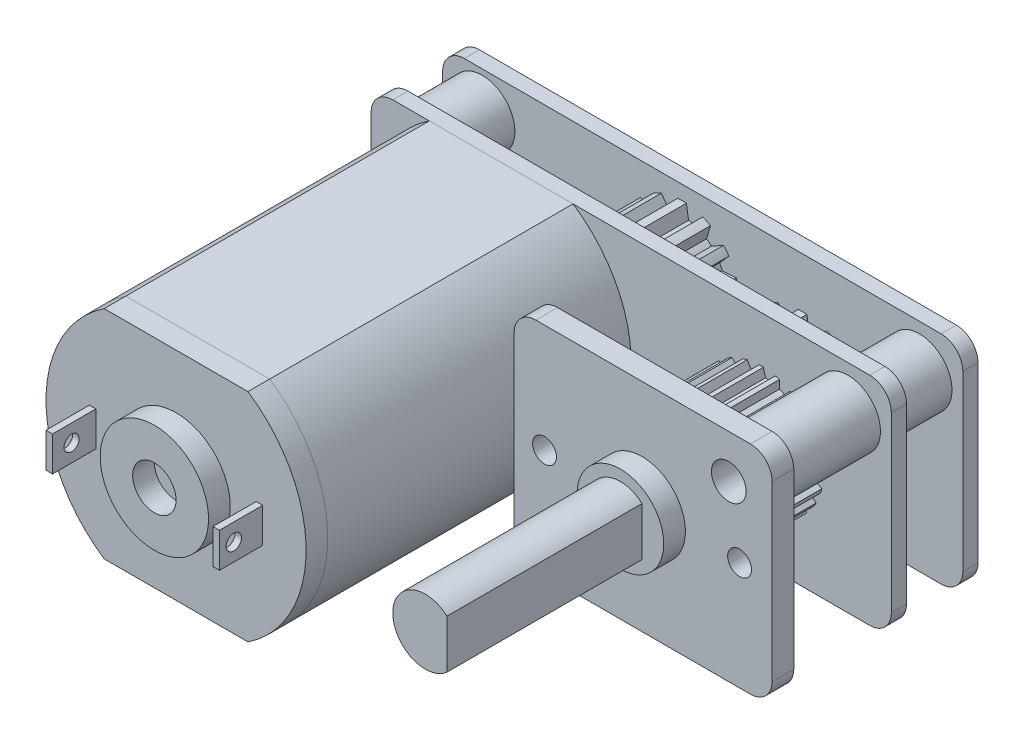
SolidWorks part; units mm, degrees
ref_plane "前视基准面" through (0, 0, 0) normal (0, 0, 1) x (1, 0, 0)
ref_plane "上视基准面" through (0, 0, 0) normal (0, 1, 0) x (1, 0, 0)
ref_plane "右视基准面" through (0, 0, 0) normal (1, 0, 0) x (0, 0, -1)
sketch "草图1" plane through (0, 0, 0) normal (0, 0, 1) x (1, 0, 0)
  line L0 (0, 0) -> (18.8291, 0) construction
  line L1 (-3.3166, 5) -> (3.3166, 5)
  line L3 (-3.3166, -5) -> (3.3166, -5)
  arc A0 (-3.3166, 5) -> (-3.3166, -5) centre (0, 0) ccw
  arc A1 (3.3166, -5) -> (3.3166, 5) centre (0, 0) ccw
  dimension "D1" = 12
  dimension "D2" = 10
extrude "凸台-拉伸1" add sketch "草图1" along normal blind 14
sketch "草图2" plane through (0, 0, 14) normal (0, 0, 1) x (1, 0, 0)
  line L2 (-3.3166, -5) -> (3.3166, -5)
  line L3 (3.3166, 5) -> (-3.3166, 5)
  line L4 (-3.3166, -5) -> (3.3166, -5)
  line L5 (3.3166, 5) -> (-3.3166, 5)
  arc A2 (-3.3166, 5) -> (-3.3166, -5) centre (0, 0) ccw
  arc A3 (3.3166, -5) -> (3.3166, 5) centre (0, 0) ccw
  arc A4 (-3.3166, 5) -> (-3.3166, -5) centre (0, 0) ccw
  arc A5 (3.3166, -5) -> (3.3166, 5) centre (0, 0) ccw
  dimension "D1" = 0
extrude "凸台-拉伸2" add sketch "草图2" along normal blind 1 separate body
sketch "草图3" plane through (0, 0, 15) normal (0, 0, 1) x (1, 0, 0)
  circle A0 centre (0, 0) radius 2.5
  circle A1 centre (0, 0) radius 1
  dimension "D1" = 5
  dimension "D2" = 2
extrude "凸台-拉伸3" add sketch "草图3" along normal blind 1
sketch "草图4" plane through (0, 0, 15) normal (0, 0, 1) x (1, 0, 0)
  line L0 (0, 0) -> (0, 3.9514) construction
  line L1 (-4, 0.8) -> (-3.7, 0.8)
  line L2 (-4, 0.8) -> (-4, -0.8)
  line L3 (-4, -0.8) -> (-3.7, -0.8)
  line L4 (-3.7, 0.8) -> (-3.7, -0.8)
  line L5 (0, 0) -> (-8.2153, 0) construction
  line L6 (3.7, 0.8) -> (3.7, -0.8)
  line L7 (4, -0.8) -> (3.7, -0.8)
  line L8 (4, 0.8) -> (4, -0.8)
  line L9 (4, 0.8) -> (3.7, 0.8)
  dimension "D1" = 1.6
  dimension "D2" = 0.3
  dimension "D3" = 4
extrude "凸台-拉伸4" add sketch "草图4" along normal blind 2 separate body
sketch "草图5" plane through (-4, 0, 0) normal (-1, 0, 0) x (0, 0, 1)
  circle A0 centre (16.1189, 0) radius 0.35
  dimension "D1" = 0.7
extrude "切除-拉伸1" cut sketch "草图5" against normal blind 1
sketch "草图6" plane through (4, 0, 0) normal (1, 0, 0) x (0, 0, -1)
  circle A0 centre (-16.3339, 0) radius 0.3561
  dimension "D1" = 0.7122
extrude "切除-拉伸2" cut sketch "草图6" against normal blind 1
sketch "草图7" plane through (0, 0, 0) normal (0, 0, -1) x (-1, 0, 0)
  line L0 (0, 0) -> (0, 7.3906) construction
  line L1 (-17, 5) -> (5, 5)
  line L2 (-18, 4) -> (-18, -4)
  line L3 (-17, -5) -> (5, -5)
  line L4 (6, 4) -> (6, -4)
  line L5 (0, 0) -> (-12.0112, 0) construction
  arc A0 (-18, -4) -> (-17, -5) centre (-17, -4) ccw
  arc A1 (5, -5) -> (6, -4) centre (5, -4) ccw
  arc A2 (6, 4) -> (5, 5) centre (5, 4) ccw
  arc A3 (-17, 5) -> (-18, 4) centre (-17, 4) ccw
  point P10 (-18, -5)
  point P15 (6, 5)
  point P18 (-18, 5)
  dimension "D3" = 1
  dimension "D1" = 10
  dimension "D2" = 24
  dimension "D4" = 6
extrude "凸台-拉伸5" add sketch "草图7" along normal blind 0.7 separate body
sketch "草图8" plane through (0, 0, -0.7) normal (0, 0, -1) x (-1, 0, 0)
  line L0 (0, 0) -> (0, 2.0594) construction
  line L1 (0, 2.1498) -> (0.1718, 1.6344)
  line L2 (0, 2.1498) -> (-0.1718, 1.6344)
  line L3 (0.447, 2.1028) -> (0.5078, 1.563)
  line L4 (0.447, 2.1028) -> (0.1718, 1.6344)
  line L5 (0.8744, 1.9639) -> (0.8217, 1.4232)
  line L6 (0.8744, 1.9639) -> (0.5078, 1.563)
  line L7 (1.2636, 1.7392) -> (1.0997, 1.2213)
  line L8 (1.2636, 1.7392) -> (0.8217, 1.4232)
  line L9 (1.5976, 1.4385) -> (1.3296, 0.966)
  line L10 (1.5976, 1.4385) -> (1.0997, 1.2213)
  line L11 (1.8618, 1.0749) -> (1.5013, 0.6684)
  line L12 (1.8618, 1.0749) -> (1.3296, 0.966)
  line L13 (2.0446, 0.6643) -> (1.6075, 0.3417)
  line L14 (2.0446, 0.6643) -> (1.5013, 0.6684)
  line L15 (2.138, 0.2247) -> (1.6434, 0)
  line L16 (2.138, 0.2247) -> (1.6075, 0.3417)
  line L17 (2.138, -0.2247) -> (1.6075, -0.3417)
  line L18 (2.138, -0.2247) -> (1.6434, 0)
  line L19 (2.0446, -0.6643) -> (1.5013, -0.6684)
  line L20 (2.0446, -0.6643) -> (1.6075, -0.3417)
  line L21 (1.8618, -1.0749) -> (1.3296, -0.966)
  line L22 (1.8618, -1.0749) -> (1.5013, -0.6684)
  line L23 (1.5976, -1.4385) -> (1.0997, -1.2213)
  line L24 (1.5976, -1.4385) -> (1.3296, -0.966)
  line L25 (1.2636, -1.7392) -> (0.8217, -1.4232)
  line L26 (1.2636, -1.7392) -> (1.0997, -1.2213)
  line L27 (0.8744, -1.9639) -> (0.5078, -1.563)
  line L28 (0.8744, -1.9639) -> (0.8217, -1.4232)
  line L29 (0.447, -2.1028) -> (0.1718, -1.6344)
  line L30 (0.447, -2.1028) -> (0.5078, -1.563)
  line L31 (0, -2.1498) -> (-0.1718, -1.6344)
  line L32 (0, -2.1498) -> (0.1718, -1.6344)
  line L33 (-0.447, -2.1028) -> (-0.5078, -1.563)
  line L34 (-0.447, -2.1028) -> (-0.1718, -1.6344)
  line L35 (-0.8744, -1.9639) -> (-0.8217, -1.4232)
  line L36 (-0.8744, -1.9639) -> (-0.5078, -1.563)
  line L37 (-1.2636, -1.7392) -> (-1.0997, -1.2213)
  line L38 (-1.2636, -1.7392) -> (-0.8217, -1.4232)
  line L39 (-1.5976, -1.4385) -> (-1.3296, -0.966)
  line L40 (-1.5976, -1.4385) -> (-1.0997, -1.2213)
  line L41 (-1.8618, -1.0749) -> (-1.5013, -0.6684)
  line L42 (-1.8618, -1.0749) -> (-1.3296, -0.966)
  line L43 (-2.0446, -0.6643) -> (-1.6075, -0.3417)
  line L44 (-2.0446, -0.6643) -> (-1.5013, -0.6684)
  line L45 (-2.138, -0.2247) -> (-1.6434, 0)
  line L46 (-2.138, -0.2247) -> (-1.6075, -0.3417)
  line L47 (-2.138, 0.2247) -> (-1.6075, 0.3417)
  line L48 (-2.138, 0.2247) -> (-1.6434, 0)
  line L49 (-2.0446, 0.6643) -> (-1.5013, 0.6684)
  line L50 (-2.0446, 0.6643) -> (-1.6075, 0.3417)
  line L51 (-1.8618, 1.0749) -> (-1.3296, 0.966)
  line L52 (-1.8618, 1.0749) -> (-1.5013, 0.6684)
  line L53 (-1.5976, 1.4385) -> (-1.0997, 1.2213)
  line L54 (-1.5976, 1.4385) -> (-1.3296, 0.966)
  line L55 (-1.2636, 1.7392) -> (-0.8217, 1.4232)
  line L56 (-1.2636, 1.7392) -> (-1.0997, 1.2213)
  line L57 (-0.8744, 1.9639) -> (-0.5078, 1.563)
  line L58 (-0.8744, 1.9639) -> (-0.8217, 1.4232)
  line L59 (-0.447, 2.1028) -> (-0.1718, 1.6344)
  line L60 (-0.447, 2.1028) -> (-0.5078, 1.563)
  point P96 (0, 0)
extrude "凸台-拉伸6" add sketch "草图8" along normal blind 2.5
sketch "草图9" plane through (0, 0, -0.7) normal (0, 0, -1) x (-1, 0, 0)
  circle A0 centre (4.1671, 3.2475) radius 1.5
  circle A1 centre (-4.1288, -3.2666) radius 1.5
  dimension "D1" = 3
  dimension "D2" = 3
extrude "凸台-拉伸7" add sketch "草图9" along normal blind 2.6
sketch "草图10" plane through (0, 0, -3.3) normal (0, 0, -1) x (-1, 0, 0)
  line L0 (0, 0) -> (0, 6.111) construction
  line L1 (-17, 5) -> (5, 5)
  line L2 (-18, 4) -> (-18, -4)
  line L3 (-17, -5) -> (5, -5)
  line L4 (6, 4) -> (6, -4)
  line L5 (0, 0) -> (8.0146, 0) construction
  arc A0 (-18, -4) -> (-17, -5) centre (-17, -4) ccw
  arc A1 (5, -5) -> (6, -4) centre (5, -4) ccw
  arc A2 (6, 4) -> (5, 5) centre (5, 4) ccw
  arc A3 (-17, 5) -> (-18, 4) centre (-17, 4) ccw
  point P10 (-18, -5)
  point P15 (6, 5)
  point P18 (-18, 5)
  dimension "D3" = 1
  dimension "D1" = 10
  dimension "D2" = 24
  dimension "D4" = 6
extrude "凸台-拉伸8" add sketch "草图10" along normal blind 0.7
sketch "草图11" plane through (0, 0, -4) normal (0, 0, -1) x (-1, 0, 0)
  line L0 (-18, 4) -> (-18, -4) construction
  line L1 (5, 5) -> (-17, 5) construction
  line L2 (-17, -5) -> (5, -5) construction
  circle A0 centre (-16, 3) radius 1.5
  circle A1 centre (-8, -3) radius 1.5
  circle A2 centre (-16, 3) radius 0.8
  circle A3 centre (-8, -3) radius 0.8
  dimension "D1" = 2
  dimension "D2" = 2
  dimension "D3" = 3
  dimension "D4" = 1.6
  dimension "D6" = 2
  dimension "D7" = 3
  dimension "D8" = 1.6
  dimension "D5" = 10
extrude "凸台-拉伸9" add sketch "草图11" against normal blind 9.5
sketch "草图17" plane through (0, 0, 0) normal (0, 0, 1) x (1, 0, 0)
  line L0 (18, 4) -> (18, -4) construction
  line L1 (-5, 5) -> (17, 5) construction
  line L2 (12, 0) -> (12, 3.9728) construction
  line L3 (11.9, 2.8644) -> (11.8, 2.492)
  line L4 (12.1, 2.8644) -> (12.2, 2.492)
  line L5 (12.6448, 2.7927) -> (12.4518, 2.4588)
  line L6 (12.8379, 2.7409) -> (12.8382, 2.3553)
  line L7 (13.3456, 2.5306) -> (13.0728, 2.2581)
  line L8 (13.5188, 2.4306) -> (13.4192, 2.0581)
  line L9 (13.9547, 2.0961) -> (13.6207, 1.9035)
  line L10 (14.0961, 1.9547) -> (13.9035, 1.6207)
  line L11 (14.4306, 1.5188) -> (14.0581, 1.4192)
  line L12 (14.5306, 1.3456) -> (14.2581, 1.0728)
  line L13 (14.7409, 0.8379) -> (14.3553, 0.8382)
  line L14 (14.7927, 0.6448) -> (14.4588, 0.4518)
  line L15 (14.8644, 0.1) -> (14.492, 0.2)
  line L16 (14.8644, -0.1) -> (14.492, -0.2)
  line L17 (14.7927, -0.6448) -> (14.4588, -0.4518)
  line L18 (14.7409, -0.8379) -> (14.3553, -0.8382)
  line L19 (14.5306, -1.3456) -> (14.2581, -1.0728)
  line L20 (14.4306, -1.5188) -> (14.0581, -1.4192)
  line L21 (14.0961, -1.9547) -> (13.9035, -1.6207)
  line L22 (13.9547, -2.0961) -> (13.6207, -1.9035)
  line L23 (13.5188, -2.4306) -> (13.4192, -2.0581)
  line L24 (13.3456, -2.5306) -> (13.0728, -2.2581)
  line L25 (12.8379, -2.7409) -> (12.8382, -2.3553)
  line L26 (12.6448, -2.7927) -> (12.4518, -2.4588)
  line L27 (12.1, -2.8644) -> (12.2, -2.492)
  line L28 (11.9, -2.8644) -> (11.8, -2.492)
  line L29 (11.3552, -2.7927) -> (11.5482, -2.4588)
  line L30 (11.1621, -2.7409) -> (11.1618, -2.3553)
  line L31 (10.6544, -2.5306) -> (10.9272, -2.2581)
  line L32 (10.4812, -2.4306) -> (10.5808, -2.0581)
  line L33 (10.0453, -2.0961) -> (10.3793, -1.9035)
  line L34 (9.9039, -1.9547) -> (10.0965, -1.6207)
  line L35 (9.5694, -1.5188) -> (9.9419, -1.4192)
  line L36 (9.4694, -1.3456) -> (9.7419, -1.0728)
  line L37 (9.2591, -0.8379) -> (9.6447, -0.8382)
  line L38 (9.2073, -0.6448) -> (9.5412, -0.4518)
  line L39 (9.1356, -0.1) -> (9.508, -0.2)
  line L40 (9.1356, 0.1) -> (9.508, 0.2)
  line L41 (9.2073, 0.6448) -> (9.5412, 0.4518)
  line L42 (9.2591, 0.8379) -> (9.6447, 0.8382)
  line L43 (9.4694, 1.3456) -> (9.7419, 1.0728)
  line L44 (9.5694, 1.5188) -> (9.9419, 1.4192)
  line L45 (9.9039, 1.9547) -> (10.0965, 1.6207)
  line L46 (10.0453, 2.0961) -> (10.3793, 1.9035)
  line L47 (10.4812, 2.4306) -> (10.5808, 2.0581)
  line L48 (10.6544, 2.5306) -> (10.9272, 2.2581)
  line L49 (11.1621, 2.7409) -> (11.1618, 2.3553)
  line L50 (11.3552, 2.7927) -> (11.5482, 2.4588)
  arc A0 (11.1618, 2.3553) -> (10.9272, 2.2581) centre (12, 0) ccw
  arc A1 (12.1, 2.8644) -> (11.9, 2.8644) centre (12, 0) ccw
  arc A2 (12.8379, 2.7409) -> (12.6448, 2.7927) centre (12, 0) ccw
  arc A3 (13.5188, 2.4306) -> (13.3456, 2.5306) centre (12, 0) ccw
  arc A4 (14.0961, 1.9547) -> (13.9547, 2.0961) centre (12, 0) ccw
  arc A5 (14.5306, 1.3456) -> (14.4306, 1.5188) centre (12, 0) ccw
  arc A6 (14.7927, 0.6448) -> (14.7409, 0.8379) centre (12, 0) ccw
  arc A7 (14.8644, -0.1) -> (14.8644, 0.1) centre (12, 0) ccw
  arc A8 (14.7409, -0.8379) -> (14.7927, -0.6448) centre (12, 0) ccw
  arc A9 (14.4306, -1.5188) -> (14.5306, -1.3456) centre (12, 0) ccw
  arc A10 (13.9547, -2.0961) -> (14.0961, -1.9547) centre (12, 0) ccw
  arc A11 (13.3456, -2.5306) -> (13.5188, -2.4306) centre (12, 0) ccw
  arc A12 (12.6448, -2.7927) -> (12.8379, -2.7409) centre (12, 0) ccw
  arc A13 (11.9, -2.8644) -> (12.1, -2.8644) centre (12, 0) ccw
  arc A14 (11.1621, -2.7409) -> (11.3552, -2.7927) centre (12, 0) ccw
  arc A15 (10.4812, -2.4306) -> (10.6544, -2.5306) centre (12, 0) ccw
  arc A16 (9.9039, -1.9547) -> (10.0453, -2.0961) centre (12, 0) ccw
  arc A17 (9.4694, -1.3456) -> (9.5694, -1.5188) centre (12, 0) ccw
  arc A18 (9.2073, -0.6448) -> (9.2591, -0.8379) centre (12, 0) ccw
  arc A19 (9.1356, 0.1) -> (9.1356, -0.1) centre (12, 0) ccw
  arc A20 (9.2591, 0.8379) -> (9.2073, 0.6448) centre (12, 0) ccw
  arc A21 (9.5694, 1.5188) -> (9.4694, 1.3456) centre (12, 0) ccw
  arc A22 (10.0453, 2.0961) -> (9.9039, 1.9547) centre (12, 0) ccw
  arc A23 (10.6544, 2.5306) -> (10.4812, 2.4306) centre (12, 0) ccw
  arc A24 (11.3552, 2.7927) -> (11.1621, 2.7409) centre (12, 0) ccw
  arc A25 (10.5808, 2.0581) -> (10.3793, 1.9035) centre (12, 0) ccw
  arc A26 (10.0965, 1.6207) -> (9.9419, 1.4192) centre (12, 0) ccw
  arc A27 (9.7419, 1.0728) -> (9.6447, 0.8382) centre (12, 0) ccw
  arc A28 (9.5412, 0.4518) -> (9.508, 0.2) centre (12, 0) ccw
  arc A29 (9.508, -0.2) -> (9.5412, -0.4518) centre (12, 0) ccw
  arc A30 (9.6447, -0.8382) -> (9.7419, -1.0728) centre (12, 0) ccw
  arc A31 (9.9419, -1.4192) -> (10.0965, -1.6207) centre (12, 0) ccw
  arc A32 (10.3793, -1.9035) -> (10.5808, -2.0581) centre (12, 0) ccw
  arc A33 (10.9272, -2.2581) -> (11.1618, -2.3553) centre (12, 0) ccw
  arc A34 (11.5482, -2.4588) -> (11.8, -2.492) centre (12, 0) ccw
  arc A35 (12.2, -2.492) -> (12.4518, -2.4588) centre (12, 0) ccw
  arc A36 (12.8382, -2.3553) -> (13.0728, -2.2581) centre (12, 0) ccw
  arc A37 (13.4192, -2.0581) -> (13.6207, -1.9035) centre (12, 0) ccw
  arc A38 (13.9035, -1.6207) -> (14.0581, -1.4192) centre (12, 0) ccw
  arc A39 (14.2581, -1.0728) -> (14.3553, -0.8382) centre (12, 0) ccw
  arc A40 (14.4588, -0.4518) -> (14.492, -0.2) centre (12, 0) ccw
  arc A41 (14.492, 0.2) -> (14.4588, 0.4518) centre (12, 0) ccw
  arc A42 (14.3553, 0.8382) -> (14.2581, 1.0728) centre (12, 0) ccw
  arc A43 (14.0581, 1.4192) -> (13.9035, 1.6207) centre (12, 0) ccw
  arc A44 (13.6207, 1.9035) -> (13.4192, 2.0581) centre (12, 0) ccw
  arc A45 (13.0728, 2.2581) -> (12.8382, 2.3553) centre (12, 0) ccw
  arc A46 (12.4518, 2.4588) -> (12.2, 2.492) centre (12, 0) ccw
  arc A47 (11.8, 2.492) -> (11.5482, 2.4588) centre (12, 0) ccw
  point P106 (12, 0)
  dimension "D1" = 6
  dimension "D2" = 5
  dimension "D3" = 5
  dimension "D4" = 0.2
  dimension "D5" = 0.4
  dimension "D6" = 24
extrude "凸台-拉伸15" add sketch "草图17" along normal blind 4.5 separate body
sketch "草图13" plane through (0, 0, 5.5) normal (0, 0, 1) x (1, 0, 0)
  line L1 (7.1, 5) -> (17, 5)
  line L2 (6.1, 4) -> (6.1, -4)
  line L3 (7.1, -5) -> (17, -5)
  line L4 (18, 4) -> (18, -4)
  circle A0 centre (16, 3) radius 0.8 construction
  circle A1 centre (16, 3) radius 0.8 construction
  circle A2 centre (8, -3) radius 1.5 construction
  circle A3 centre (8, -3) radius 0.8 construction
  circle A4 centre (16, 3) radius 0.8
  circle A5 centre (8, -3) radius 0.8
  arc A6 (6.1, 4) -> (7.1, 5) centre (7.1, 4) cw
  arc A7 (18, 4) -> (17, 5) centre (17, 4) ccw
  arc A8 (17, -5) -> (18, -4) centre (17, -4) ccw
  arc A9 (6.1, -4) -> (7.1, -5) centre (7.1, -4) ccw
  dimension "D2" = 2
  dimension "D5" = 1
  dimension "D6" = 1
  dimension "D7" = 1
  dimension "D8" = 1
  dimension "D1" = 2
  dimension "D3" = 2
  dimension "D4" = 1.9
extrude "凸台-拉伸12" add sketch "草图13" against normal blind 1
sketch "草图14" plane through (0, 0, 5.5) normal (0, 0, 1) x (1, 0, 0)
  line L0 (18, -4) -> (18, 4) construction
  line L1 (17, 5) -> (7.1, 5) construction
  circle A0 centre (12, 0) radius 2
  dimension "D1" = 4
  dimension "D2" = 6
  dimension "D3" = 5
extrude "凸台-拉伸13" add sketch "草图14" along normal blind 1
sketch "草图15" plane through (0, 0, 6.5) normal (0, 0, 1) x (1, 0, 0)
  line L0 (13, 1.118) -> (13, -1.118)
  arc A0 (13, 1.118) -> (13, -1.118) centre (12, 0) ccw
  dimension "D1" = 3
  dimension "D2" = 1
extrude "凸台-拉伸14" add sketch "草图15" along normal blind 9 separate body
sketch "草图18" plane through (0, 0, -3.3) normal (0, 0, 1) x (1, 0, 0)
  line L0 (10.6064, -0.5194) -> (10.6064, 3.2639) construction
  line L1 (10.4066, 2.6777) -> (10.2871, 1.9602)
  line L2 (10.8062, 2.6777) -> (10.9257, 1.9602)
  line L3 (11.7243, 2.4826) -> (11.3232, 1.8757)
  line L4 (12.0893, 2.3201) -> (11.9066, 1.6159)
  line L5 (12.8486, 1.7684) -> (12.2354, 1.3771)
  line L6 (13.116, 1.4714) -> (12.6627, 0.9025)
  line L7 (13.5853, 0.6586) -> (12.8659, 0.5505)
  line L8 (13.7088, 0.2786) -> (13.0633, -0.0568)
  line L9 (13.8069, -0.6548) -> (13.1057, -0.461)
  line L10 (13.7651, -1.0523) -> (13.039, -1.0961)
  line L11 (13.4751, -1.9449) -> (12.9134, -1.4826)
  line L12 (13.2753, -2.291) -> (12.5941, -2.0357)
  line L13 (12.6473, -2.9884) -> (12.3222, -2.3377)
  line L14 (12.324, -3.2233) -> (11.8055, -2.713)
  line L15 (11.4666, -3.6051) -> (11.4343, -2.8783)
  line L16 (11.0757, -3.6881) -> (10.8096, -3.0111)
  line L17 (10.1372, -3.6881) -> (10.4032, -3.0111)
  line L18 (9.7463, -3.6051) -> (9.7786, -2.8783)
  line L19 (8.8889, -3.2233) -> (9.4073, -2.713)
  line L20 (8.5656, -2.9884) -> (8.8907, -2.3377)
  line L21 (7.9376, -2.291) -> (8.6188, -2.0357)
  line L22 (7.7377, -1.9449) -> (8.2994, -1.4826)
  line L23 (7.4477, -1.0523) -> (8.1739, -1.0961)
  line L24 (7.406, -0.6548) -> (8.1071, -0.461)
  line L25 (7.5041, 0.2786) -> (8.1496, -0.0568)
  line L26 (7.6275, 0.6586) -> (8.3469, 0.5505)
  line L27 (8.0968, 1.4714) -> (8.5501, 0.9025)
  line L28 (8.3642, 1.7684) -> (8.9774, 1.3771)
  line L29 (9.1235, 2.3201) -> (9.3062, 1.6159)
  line L30 (9.4886, 2.4826) -> (9.8896, 1.8757)
  line L31 (5.0458, 1.7345) -> (5.0458, 6.0072) construction
  line L32 (4.8473, 4.3408) -> (4.7438, 3.7116)
  line L33 (5.2444, 4.3408) -> (5.3479, 3.7116)
  line L34 (5.9978, 4.1689) -> (5.6315, 3.6468)
  line L35 (6.3556, 3.9966) -> (6.1758, 3.3847)
  line L36 (6.9597, 3.5148) -> (6.4032, 3.2033)
  line L37 (7.2074, 3.2043) -> (6.7799, 2.731)
  line L38 (7.5426, 2.508) -> (6.9061, 2.4689)
  line L39 (7.631, 2.1209) -> (7.0405, 1.88)
  line L40 (7.631, 1.3481) -> (7.0405, 1.589)
  line L41 (7.5426, 0.9609) -> (6.9061, 1.0001)
  line L42 (7.2074, 0.2647) -> (6.7799, 0.738)
  line L43 (6.9597, -0.0458) -> (6.4032, 0.2657)
  line L44 (6.3556, -0.5276) -> (6.1758, 0.0843)
  line L45 (5.9978, -0.6999) -> (5.6315, -0.1778)
  line L46 (5.2444, -0.8718) -> (5.3479, -0.2426)
  line L47 (4.8473, -0.8718) -> (4.7438, -0.2426)
  line L48 (4.0939, -0.6999) -> (4.4602, -0.1778)
  line L49 (3.7361, -0.5276) -> (3.9159, 0.0843)
  line L50 (3.1319, -0.0458) -> (3.6884, 0.2657)
  line L51 (2.8843, 0.2647) -> (3.3118, 0.738)
  line L52 (2.5491, 0.9609) -> (3.1856, 1.0001)
  line L53 (2.4607, 1.3481) -> (3.0511, 1.589)
  line L54 (2.4607, 2.1209) -> (3.0511, 1.88)
  line L55 (2.5491, 2.508) -> (3.1856, 2.4689)
  line L56 (2.8843, 3.2043) -> (3.3118, 2.731)
  line L57 (3.1319, 3.5148) -> (3.6884, 3.2033)
  line L58 (3.7361, 3.9966) -> (3.9159, 3.3847)
  line L59 (4.0939, 4.1689) -> (4.4602, 3.6468)
  arc A0 (3.9159, 3.3847) -> (3.6884, 3.2033) centre (5.0458, 1.7345) ccw
  arc A1 (9.3062, 1.6159) -> (8.9774, 1.3771) centre (10.6064, -0.5194) ccw
  arc A2 (10.8062, 2.6777) -> (10.4066, 2.6777) centre (10.6064, -0.5194) ccw
  arc A3 (5.2444, 4.3408) -> (4.8473, 4.3408) centre (5.0458, 1.7345) ccw
  arc A4 (12.0893, 2.3201) -> (11.7243, 2.4826) centre (10.6064, -0.5194) ccw
  arc A5 (13.116, 1.4714) -> (12.8486, 1.7684) centre (10.6064, -0.5194) ccw
  arc A6 (13.7088, 0.2786) -> (13.5853, 0.6586) centre (10.6064, -0.5194) ccw
  arc A7 (13.7651, -1.0523) -> (13.8069, -0.6548) centre (10.6064, -0.5194) ccw
  arc A8 (13.2753, -2.291) -> (13.4751, -1.9449) centre (10.6064, -0.5194) ccw
  arc A9 (12.324, -3.2233) -> (12.6473, -2.9884) centre (10.6064, -0.5194) ccw
  arc A10 (11.0757, -3.6881) -> (11.4666, -3.6051) centre (10.6064, -0.5194) ccw
  arc A11 (9.7463, -3.6051) -> (10.1372, -3.6881) centre (10.6064, -0.5194) ccw
  arc A12 (8.5656, -2.9884) -> (8.8889, -3.2233) centre (10.6064, -0.5194) ccw
  arc A13 (7.7377, -1.9449) -> (7.9376, -2.291) centre (10.6064, -0.5194) ccw
  arc A14 (7.406, -0.6548) -> (7.4477, -1.0523) centre (10.6064, -0.5194) ccw
  arc A15 (7.6275, 0.6586) -> (7.5041, 0.2786) centre (10.6064, -0.5194) ccw
  arc A16 (8.3642, 1.7684) -> (8.0968, 1.4714) centre (10.6064, -0.5194) ccw
  arc A17 (9.4886, 2.4826) -> (9.1235, 2.3201) centre (10.6064, -0.5194) ccw
  arc A18 (10.2871, 1.9602) -> (9.8896, 1.8757) centre (10.6064, -0.5194) ccw
  arc A19 (11.3232, 1.8757) -> (10.9257, 1.9602) centre (10.6064, -0.5194) ccw
  arc A20 (12.2354, 1.3771) -> (11.9066, 1.6159) centre (10.6064, -0.5194) ccw
  arc A21 (12.8659, 0.5505) -> (12.6627, 0.9025) centre (10.6064, -0.5194) ccw
  arc A22 (13.1057, -0.461) -> (13.0633, -0.0568) centre (10.6064, -0.5194) ccw
  arc A23 (12.9134, -1.4826) -> (13.039, -1.0961) centre (10.6064, -0.5194) ccw
  arc A24 (12.3222, -2.3377) -> (12.5941, -2.0357) centre (10.6064, -0.5194) ccw
  arc A25 (11.4343, -2.8783) -> (11.8055, -2.713) centre (10.6064, -0.5194) ccw
  arc A26 (10.4032, -3.0111) -> (10.8096, -3.0111) centre (10.6064, -0.5194) ccw
  arc A27 (9.4073, -2.713) -> (9.7786, -2.8783) centre (10.6064, -0.5194) ccw
  arc A28 (8.6188, -2.0357) -> (8.8907, -2.3377) centre (10.6064, -0.5194) ccw
  arc A29 (8.1739, -1.0961) -> (8.2994, -1.4826) centre (10.6064, -0.5194) ccw
  arc A30 (8.1496, -0.0568) -> (8.1071, -0.461) centre (10.6064, -0.5194) ccw
  arc A31 (8.5501, 0.9025) -> (8.3469, 0.5505) centre (10.6064, -0.5194) ccw
  arc A32 (6.3556, 3.9966) -> (5.9978, 4.1689) centre (5.0458, 1.7345) ccw
  arc A33 (7.2074, 3.2043) -> (6.9597, 3.5148) centre (5.0458, 1.7345) ccw
  arc A34 (7.631, 2.1209) -> (7.5426, 2.508) centre (5.0458, 1.7345) ccw
  arc A35 (7.5426, 0.9609) -> (7.631, 1.3481) centre (5.0458, 1.7345) ccw
  arc A36 (6.9597, -0.0458) -> (7.2074, 0.2647) centre (5.0458, 1.7345) ccw
  arc A37 (5.9978, -0.6999) -> (6.3556, -0.5276) centre (5.0458, 1.7345) ccw
  arc A38 (4.8473, -0.8718) -> (5.2444, -0.8718) centre (5.0458, 1.7345) ccw
  arc A39 (3.7361, -0.5276) -> (4.0939, -0.6999) centre (5.0458, 1.7345) ccw
  arc A40 (2.8843, 0.2647) -> (3.1319, -0.0458) centre (5.0458, 1.7345) ccw
  arc A41 (2.4607, 1.3481) -> (2.5491, 0.9609) centre (5.0458, 1.7345) ccw
  arc A42 (2.5491, 2.508) -> (2.4607, 2.1209) centre (5.0458, 1.7345) ccw
  arc A43 (3.1319, 3.5148) -> (2.8843, 3.2043) centre (5.0458, 1.7345) ccw
  arc A44 (4.0939, 4.1689) -> (3.7361, 3.9966) centre (5.0458, 1.7345) ccw
  arc A45 (4.7438, 3.7116) -> (4.4602, 3.6468) centre (5.0458, 1.7345) ccw
  arc A46 (5.6315, 3.6468) -> (5.3479, 3.7116) centre (5.0458, 1.7345) ccw
  arc A47 (6.4032, 3.2033) -> (6.1758, 3.3847) centre (5.0458, 1.7345) ccw
  arc A48 (6.9061, 2.4689) -> (6.7799, 2.731) centre (5.0458, 1.7345) ccw
  arc A49 (7.0405, 1.589) -> (7.0405, 1.88) centre (5.0458, 1.7345) ccw
  arc A50 (6.7799, 0.738) -> (6.9061, 1.0001) centre (5.0458, 1.7345) ccw
  arc A51 (6.1758, 0.0843) -> (6.4032, 0.2657) centre (5.0458, 1.7345) ccw
  arc A52 (5.3479, -0.2426) -> (5.6315, -0.1778) centre (5.0458, 1.7345) ccw
  arc A53 (4.4602, -0.1778) -> (4.7438, -0.2426) centre (5.0458, 1.7345) ccw
  arc A54 (3.6884, 0.2657) -> (3.9159, 0.0843) centre (5.0458, 1.7345) ccw
  arc A55 (3.1856, 1.0001) -> (3.3118, 0.738) centre (5.0458, 1.7345) ccw
  arc A56 (3.0511, 1.88) -> (3.0511, 1.589) centre (5.0458, 1.7345) ccw
  arc A57 (3.3118, 2.731) -> (3.1856, 2.4689) centre (5.0458, 1.7345) ccw
  point P69 (10.6064, -0.5194)
  point P125 (5.0458, 1.7345)
  dimension "D1" = 5
  dimension "D2" = 4
  dimension "D4" = 15
  dimension "D3" = 6
  dimension "D5" = 14
extrude "凸台-拉伸16" add sketch "草图18" along normal blind 2 separate body
sketch "草图19" plane through (0, 0, 5.5) normal (0, 0, 1) x (1, 0, 0)
  line L0 (12, 0) -> (12, 6.9635) construction
  line L1 (7.5, 0) -> (16.5, 0) construction
  circle A0 centre (7.5, 0) radius 0.55
  circle A1 centre (16.5, 0) radius 0.55
  dimension "D1" = 9
  dimension "D2" = 1.1
extrude "切除-拉伸3" cut sketch "草图19" against normal blind 2
cosmetic thread "装饰螺纹线1" parameters "D2"=1.6
cosmetic thread "装饰螺纹线2" parameters "D2"=1.6
